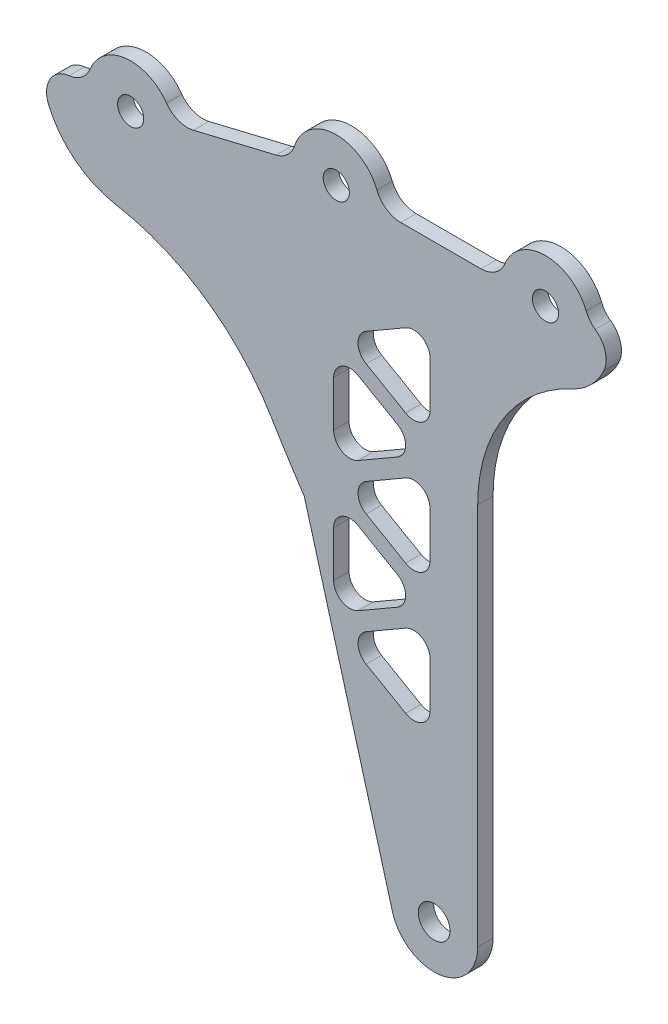
SolidWorks part; units mm, degrees
ref_plane "前视基准面" through (0, 0, 0) normal (0, 0, 1) x (1, 0, 0)
ref_plane "上视基准面" through (0, 0, 0) normal (0, 1, 0) x (1, 0, 0)
ref_plane "右视基准面" through (0, 0, 0) normal (1, 0, 0) x (0, 0, -1)
sketch "草图1" plane through (0, 0, 0) normal (0, 0, 1) x (1, 0, 0)
  line L0 (-441.1092, 106.5112) -> (-441.1092, 115.4134)
  line L1 (-445.8717, 118.1631) -> (-453.5813, 113.712)
  line L2 (-453.5813, 108.2127) -> (-445.8717, 103.7616)
  line L3 (-455.1688, 116.4616) -> (-447.4592, 120.9127)
  line L4 (-447.4592, 126.412) -> (-455.1688, 130.8631)
  line L5 (-459.9313, 128.1134) -> (-459.9313, 119.2112)
  line L6 (-441.1092, 157.3112) -> (-441.1092, 166.2134)
  line L7 (-445.8717, 168.9631) -> (-453.5813, 164.512)
  line L8 (-453.5813, 159.0127) -> (-445.8717, 154.5616)
  line L9 (-441.1092, 131.9112) -> (-441.1092, 140.8134)
  line L10 (-445.8717, 143.5631) -> (-453.5813, 139.112)
  line L11 (-453.5813, 133.6127) -> (-445.8717, 129.1616)
  line L12 (-455.1688, 141.8616) -> (-447.4592, 146.3127)
  line L13 (-447.4592, 151.812) -> (-455.1688, 156.2631)
  line L14 (-459.9313, 153.5134) -> (-459.9313, 144.6112)
  line L15 (-431.8, 71.2869) -> (-431.8, 146.05)
  line L16 (-448.6121, 69.5095) -> (-465.668, 130.5974)
  line L17 (-487.3174, 181.6444) -> (-471.1689, 185.519)
  line L18 (-446.8251, 186.2869) -> (-431.1583, 186.2869)
  circle A0 centre (-459.4188, 186.2869) radius 2.5527
  circle A1 centre (-418.5645, 186.2869) radius 2.5527
  circle A2 centre (-499.5636, 178.7061) radius 2.5527
  circle A3 centre (-440.3, 71.2869) radius 3.1
  arc A4 (-445.8717, 103.7616) -> (-441.1092, 106.5112) centre (-444.2842, 106.5112) ccw
  arc A5 (-441.1092, 115.4134) -> (-445.8717, 118.1631) centre (-444.2842, 115.4134) ccw
  arc A6 (-453.5813, 113.712) -> (-453.5813, 108.2127) centre (-451.9938, 110.9623) ccw
  arc A7 (-459.9313, 119.2112) -> (-455.1688, 116.4616) centre (-456.7563, 119.2112) ccw
  arc A8 (-447.4592, 120.9127) -> (-447.4592, 126.412) centre (-449.0467, 123.6623) ccw
  arc A9 (-455.1688, 130.8631) -> (-459.9313, 128.1134) centre (-456.7563, 128.1134) ccw
  arc A10 (-445.8717, 154.5616) -> (-441.1092, 157.3112) centre (-444.2842, 157.3112) ccw
  arc A11 (-441.1092, 166.2134) -> (-445.8717, 168.9631) centre (-444.2842, 166.2134) ccw
  arc A12 (-453.5813, 164.512) -> (-453.5813, 159.0127) centre (-451.9938, 161.7623) ccw
  arc A13 (-445.8717, 129.1616) -> (-441.1092, 131.9112) centre (-444.2842, 131.9112) ccw
  arc A14 (-441.1092, 140.8134) -> (-445.8717, 143.5631) centre (-444.2842, 140.8134) ccw
  arc A15 (-453.5813, 139.112) -> (-453.5813, 133.6127) centre (-451.9938, 136.3623) ccw
  arc A16 (-459.9313, 144.6112) -> (-455.1688, 141.8616) centre (-456.7563, 144.6112) ccw
  arc A17 (-447.4592, 146.3127) -> (-447.4592, 151.812) centre (-449.0467, 149.0623) ccw
  arc A18 (-455.1688, 156.2631) -> (-459.9313, 153.5134) centre (-456.7563, 153.5134) ccw
  arc A19 (-413.3218, 174.8931) -> (-431.8, 146.05) centre (-400.05, 146.05) ccw
  arc A20 (-448.6121, 69.5095) -> (-431.8, 71.2869) centre (-440.3, 71.2869) ccw
  arc A21 (-471.9549, 140.4744) -> (-465.668, 130.5974) centre (-300.1629, 242.883) ccw
  arc A22 (-471.9549, 140.4744) -> (-502.5441, 161.511) centre (-510.1356, 117.7141) ccw
  arc A23 (-515.5875, 171.7931) -> (-502.5441, 161.511) centre (-499.5636, 178.7061) ccw
  arc A24 (-511.577, 178.7399) -> (-515.5875, 171.7931) centre (-510.9966, 173.7737) ccw
  arc A25 (-511.577, 178.7399) -> (-507.5102, 181.8611) centre (-512.1574, 183.7061) ccw
  arc A26 (-492.5724, 183.6281) -> (-507.5102, 181.8611) centre (-499.5636, 178.7061) ccw
  arc A27 (-492.5724, 183.6281) -> (-487.3174, 181.6444) centre (-488.484, 186.5064) ccw
  arc A28 (-471.1689, 185.519) -> (-467.5692, 188.8703) centre (-472.3355, 190.381) ccw
  arc A29 (-451.4722, 189.4418) -> (-467.5692, 188.8703) centre (-459.4188, 186.2869) ccw
  arc A30 (-451.4722, 189.4418) -> (-446.8251, 186.2869) centre (-446.8251, 191.2869) ccw
  arc A31 (-431.1583, 186.2869) -> (-426.5111, 189.4418) centre (-431.1583, 191.2869) ccw
  arc A32 (-410.6179, 189.4417) -> (-426.5111, 189.4418) centre (-418.5645, 186.2869) ccw
  arc A33 (-410.6179, 189.4417) -> (-408.8478, 187.1973) centre (-405.9707, 191.2866) ccw
  arc A34 (-407.1908, 181.0008) -> (-408.8478, 187.1973) centre (-411.725, 183.1081) ccw
  arc A35 (-413.3218, 174.8931) -> (-407.1908, 181.0008) centre (-418.5645, 186.2869) ccw
  dimension "D2" = 8.5
  dimension "D1" = 115
extrude "凸台-拉伸1" add sketch "草图1" along normal blind 3
